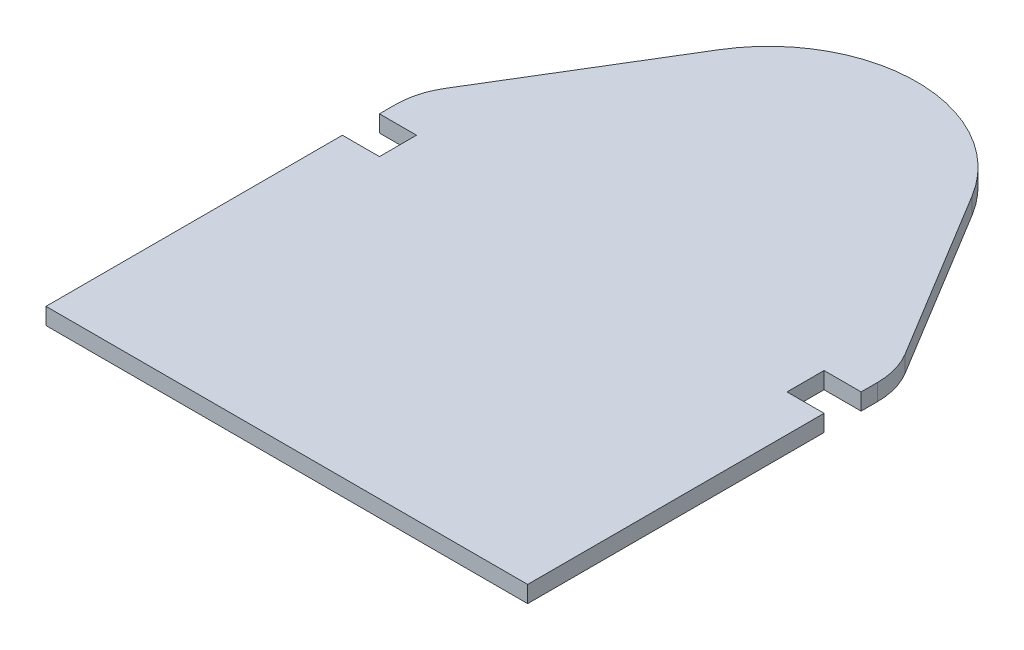
SolidWorks part; units mm, degrees
ref_plane "정면" through (0, 0, 0) normal (0, 0, 1) x (1, 0, 0)
ref_plane "윗면" through (0, 0, 0) normal (0, 1, 0) x (1, 0, 0)
ref_plane "우측면" through (0, 0, 0) normal (1, 0, 0) x (0, 0, -1)
sketch "스케치1" plane through (0, 0, 0) normal (0, 1, 0) x (1, 0, 0)
  line L0 (-65, 25) -> (-34.1944, 75.7544)
  line L2 (-65, 25) -> (-65, -75)
  line L3 (-65, -75) -> (65, -75)
  line L4 (65, 25) -> (65, -75)
  line L7 (65, 25) -> (34.1944, 75.7544)
  arc A0 (34.1944, 75.7544) -> (-34.1944, 75.7544) centre (0, 55) ccw
  point P0 (0, 0)
  point P2 (0, 0)
  point P4 (0, -75)
  dimension "D2" = 80
  dimension "D4" = 130
  dimension "D1" = 100
  dimension "D3" = 130
extrude "보스-돌출1" add sketch "스케치1" along normal blind 4.5
fillet "필렛1" radius 20 2 edges at (65, 2.25, -25) (-65, 2.25, -25)
sketch "스케치2" plane through (0, 4.5, 0) normal (0, 1, 0) x (1, 0, 0)
  line L0 (-65, 19.4054) -> (-65, -75) construction
  line L1 (-65, 15) -> (-55, 15)
  line L2 (-65, 15) -> (-65, 5)
  line L3 (-65, 5) -> (-55, 5)
  line L4 (-55, 15) -> (-55, 5)
  line L5 (65, -75) -> (65, 19.4054) construction
  line L6 (65, 15) -> (55, 15)
  line L7 (65, 15) -> (65, 5)
  line L8 (65, 5) -> (55, 5)
  line L9 (55, 15) -> (55, 5)
  line L10 (-65, -75) -> (65, -75) construction
  dimension "D1" = 10
  dimension "D2" = 10
  dimension "D3" = 80
extrude "컷-돌출1" cut sketch "스케치2" against normal through all
